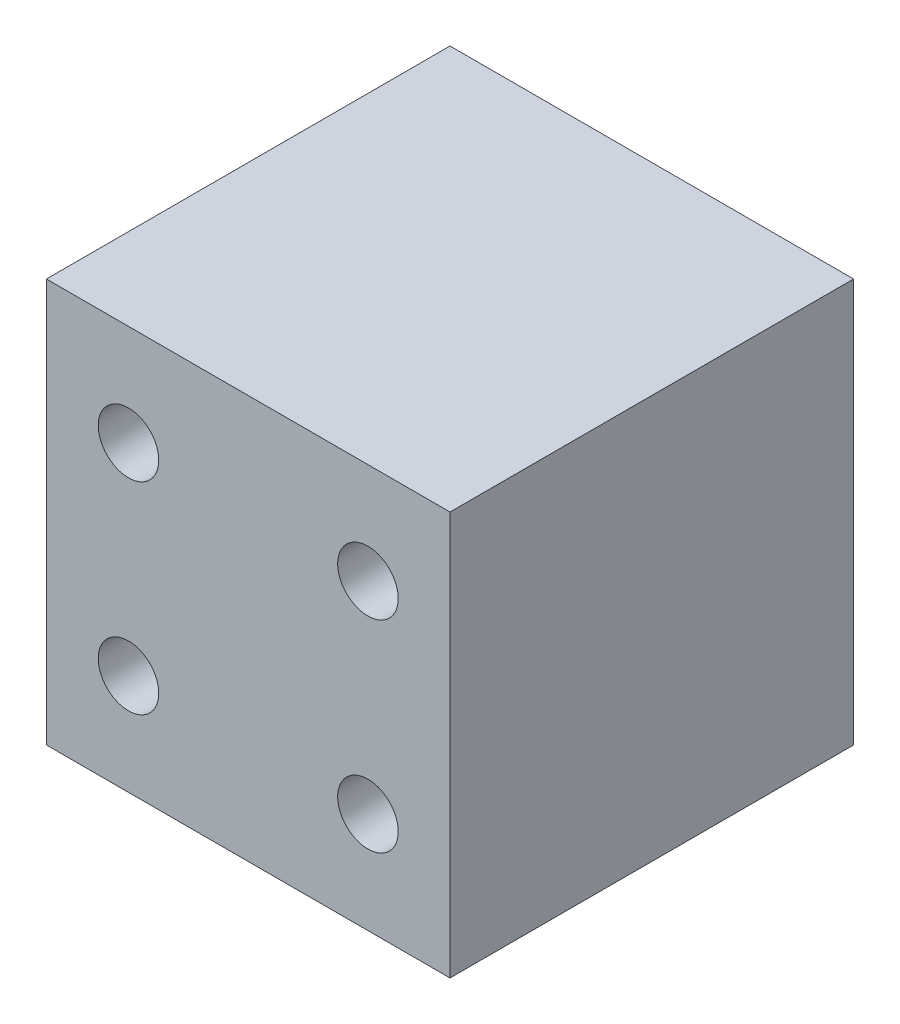
SolidWorks part; units mm, degrees
ref_plane "前视基准面" through (0, 0, 0) normal (0, 0, 1) x (1, 0, 0)
ref_plane "上视基准面" through (0, 0, 0) normal (0, 1, 0) x (1, 0, 0)
ref_plane "右视基准面" through (0, 0, 0) normal (1, 0, 0) x (0, 0, -1)
sketch "草图1" plane through (0, 0, 0) normal (0, 0, 1) x (1, 0, 0)
  line L1 (-15, 15) -> (15, 15)
  line L2 (-15, 15) -> (-15, -15)
  line L3 (-15, -15) -> (15, -15)
  line L4 (15, 15) -> (15, -15)
  line L5 (0, -15) -> (0, 15) construction
  line L6 (-15, 0) -> (15, 0) construction
  point P0 (0, 0)
  dimension "D1" = 30
  dimension "D2" = 30
extrude "凸台-拉伸1" add sketch "草图1" along normal blind 30
sketch "草图3" plane through (0, 0, 30) normal (0, 0, 1) x (1, 0, 0)
  line L0 (-15, 15) -> (15, -15)
  line L1 (15, 15) -> (-15, -15)
  point P8 (0, 0)
sketch "草图4" plane through (0, 0, 30) normal (0, 0, 1) x (1, 0, 0)
  circle A0 centre (8.9, 7.5) radius 2.25
  circle A1 centre (8.9, -7.5) radius 2.25
  circle A2 centre (-8.9, 7.5) radius 2.25
  circle A3 centre (-8.9, -7.5) radius 2.25
extrude "切除-拉伸2" cut sketch "草图4" against normal through all
